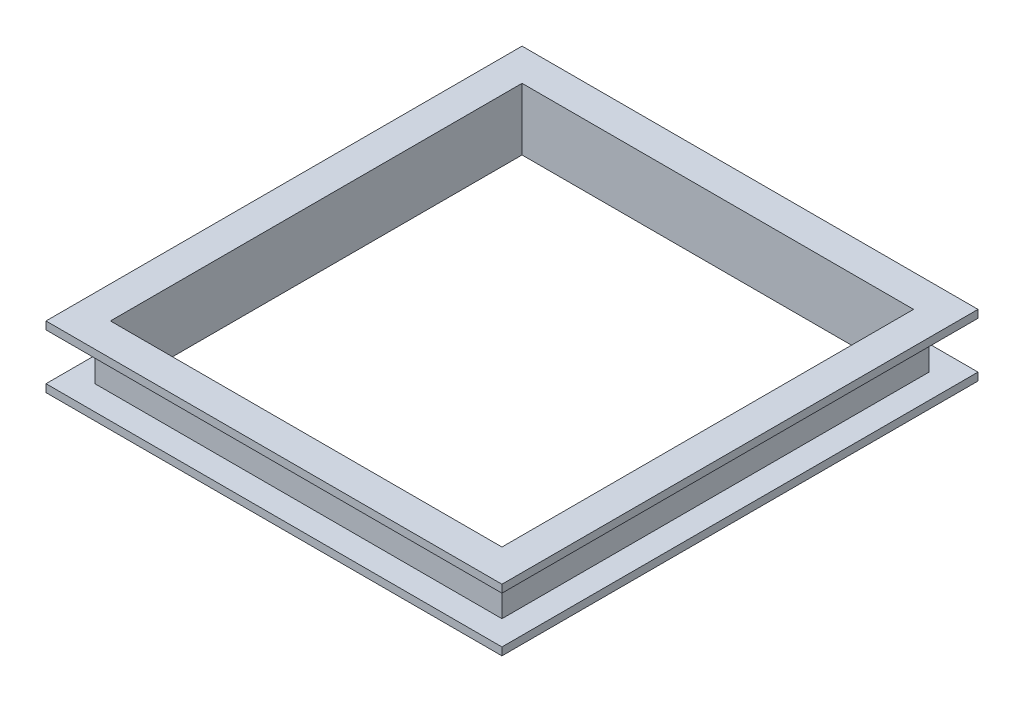
SolidWorks part; units mm, degrees
ref_plane "Front Plane" through (0, 0, 0) normal (0, 0, 1) x (1, 0, 0)
ref_plane "Top Plane" through (0, 0, 0) normal (0, 1, 0) x (1, 0, 0)
ref_plane "Right Plane" through (0, 0, 0) normal (1, 0, 0) x (0, 0, -1)
sketch "Sketch1" plane through (0, 0, 0) normal (0, 1, 0) x (1, 0, 0)
  line L0 (50.45, 60.04) -> (57.45, 60.04)
  line L1 (0, 0) -> (50.45, 0)
  line L2 (0, 0) -> (0, 53.04)
  line L3 (0, 53.04) -> (50.45, 53.04)
  line L4 (50.45, 0) -> (50.45, 53.04)
  line L11 (0, 60.04) -> (50.45, 60.04)
  line L12 (57.45, 60.04) -> (57.45, 53.04)
  line L13 (57.45, 0) -> (57.45, 53.04)
  line L14 (57.45, 0) -> (57.45, -7)
  line L15 (57.45, -7) -> (50.45, -7)
  line L16 (0, -7) -> (50.45, -7)
  line L17 (0, -7) -> (-7, -7)
  line L18 (-7, -7) -> (-7, 53.04)
  line L19 (0, 60.04) -> (-7, 60.04)
  line L20 (-7, 60.04) -> (-7, 53.04)
extrude "Boss-Extrude1" add sketch "Sketch1" along normal blind 8
sketch "Sketch2" plane through (0, 0, 7) normal (0, 0, 1) x (1, 0, 0)
  line L1 (-7, 8) -> (-7, 0) construction
  line L3 (-7, 7) -> (72.5726, 7)
  line L4 (72.5726, 7) -> (72.5726, 1)
  line L5 (72.5726, 1) -> (-15.0831, 1)
  line L6 (-15.0831, 1) -> (-15.0831, 7)
  line L7 (-15.0831, 7) -> (-7, 7)
extrude "Cut-Extrude1" cut sketch "Sketch2" against normal blind 6
sketch "Sketch3" plane through (-7, 0, 0) normal (-1, 0, 0) x (0, 0, 1)
  line L0 (1, 7) -> (-62.4879, 7)
  line L1 (1, 1) -> (-62.4879, 1)
  line L2 (-62.4879, 1) -> (-62.4879, 7)
  line L3 (1, 7) -> (11.1147, 7)
  line L4 (11.1147, 7) -> (11.1147, 1)
  line L5 (11.1147, 1) -> (1, 1)
extrude "Cut-Extrude2" cut sketch "Sketch3" against normal blind 6
sketch "Sketch4" plane through (0, 0, -60.04) normal (0, 0, -1) x (-1, 0, 0)
  line L0 (1, 7) -> (-63.69, 7)
  line L1 (1, 1) -> (11.838, 1)
  line L2 (11.838, 1) -> (11.838, 7)
  line L3 (11.838, 7) -> (1, 7)
  line L4 (1, 1) -> (-63.69, 1)
  line L5 (-63.69, 1) -> (-63.69, 7)
extrude "Cut-Extrude3" cut sketch "Sketch4" against normal blind 6
sketch "Sketch5" plane through (57.45, 0, 0) normal (1, 0, 0) x (0, 0, -1)
  line L0 (-1, 7) -> (54.04, 7)
  line L1 (54.04, 7) -> (62.0723, 7)
  line L2 (-1, 7) -> (-8.754, 7)
  line L3 (-1, 1) -> (-8.754, 1)
  line L4 (-8.754, 1) -> (-8.754, 7)
  line L5 (-1, 1) -> (62.0723, 1)
  line L6 (62.0723, 1) -> (62.0723, 7)
extrude "Cut-Extrude4" cut sketch "Sketch5" against normal blind 6
sketch "Sketch6" plane through (0, 8, 0) normal (0, 1, 0) x (1, 0, 0)
  line L0 (-7, -7) -> (-7, 60.04)
  line L1 (-7, 60.04) -> (57.45, 60.04)
  line L2 (57.45, 60.04) -> (57.45, -7)
  line L3 (57.45, -7) -> (-7, -7)
  line L8 (-4.1506, 26.52) -> (-4.1506, 57.19)
  line L9 (-4.1506, 57.19) -> (54.6, 57.19)
  line L10 (54.6, 57.19) -> (54.6, -4.15)
  line L11 (54.6, -4.15) -> (-4.1506, -4.15)
  line L12 (-4.1506, -4.15) -> (-4.1506, 26.52)
extrude "Cut-Extrude5" cut sketch "Sketch6" against normal blind 19 and the other way blind 21
